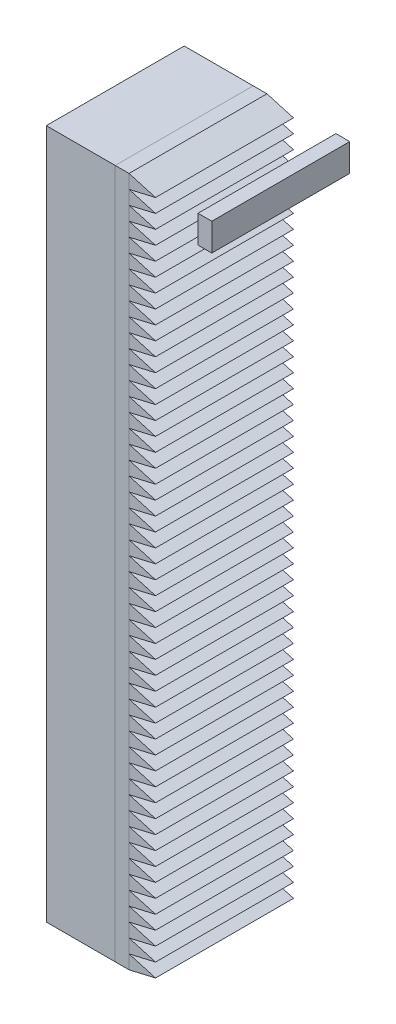
SolidWorks part; units mm, degrees
ref_plane "前基準面" through (0, 0, 0) normal (0, 0, 1) x (1, 0, 0)
ref_plane "上基準面" through (0, 0, 0) normal (0, 1, 0) x (1, 0, 0)
ref_plane "右基準面" through (0, 0, 0) normal (1, 0, 0) x (0, 0, -1)
sketch "草圖2" plane through (0, 0, 0) normal (0, 0, 1) x (1, 0, 0)
  line L1 (50, 500) -> (60, 500)
  line L2 (50, 500) -> (50, 480)
  line L3 (50, 480) -> (60, 480)
  line L4 (60, 500) -> (60, 480)
  dimension "D1" = 20
  dimension "D2" = 10
  dimension "D3" = 50
  dimension "D4" = 480
extrude "填料-伸長2" add sketch "草圖2" along normal blind 100 separate body
sketch "草圖1" plane through (0, 0, 0) normal (0, 0, 1) x (1, 0, 0)
  line L0 (0, 0) -> (0, 10)
  line L1 (0, 10) -> (19.2252, 4.4873)
  line L3 (19.2252, 4.4873) -> (0, 0)
  dimension "D1" = 10
  dimension "D2" = 20
  dimension "D4" = 74
extrude "填料-伸長1" add sketch "草圖1" along normal blind 100
pattern_linear "直線複製排列1" count 50 spacing 10 along (0, 1, 0) of "填料-伸長1"
sketch "草圖5" plane through (0, 0, 0) normal (0, 0, 1) x (1, 0, 0)
  line L1 (0, 0) -> (-10, 0)
  line L2 (0, 0) -> (0, 500)
  line L3 (0, 500) -> (-10, 500)
  line L4 (-10, 0) -> (-10, 500)
  dimension "D1" = 500
  dimension "D2" = 10
extrude "填料-伸長3" add sketch "草圖5" along normal blind 100 separate body
sketch "草圖6" plane through (0, 0, 0) normal (0, 0, 1) x (1, 0, 0)
  line L1 (-10, 0) -> (-60, 0)
  line L2 (-10, 0) -> (-10, 500)
  line L3 (-10, 500) -> (-60, 500)
  line L4 (-60, 0) -> (-60, 500)
  dimension "D1" = 500
  dimension "D2" = 50
extrude "填料-伸長5" add sketch "草圖6" along normal blind 100 separate body
